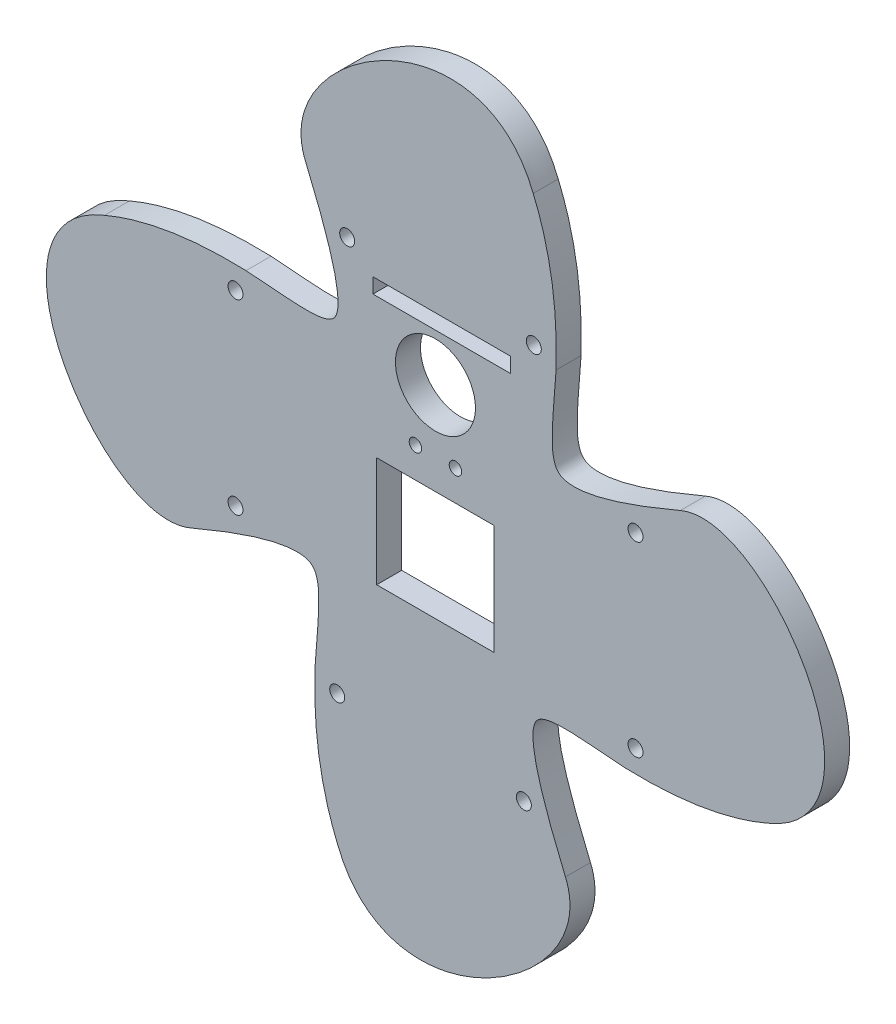
SolidWorks part; units mm, degrees
ref_plane "Front Plane" through (0, 0, 0) normal (0, 0, 1) x (1, 0, 0)
ref_plane "Top Plane" through (0, 0, 0) normal (0, 1, 0) x (1, 0, 0)
ref_plane "Right Plane" through (0, 0, 0) normal (1, 0, 0) x (0, 0, -1)
sketch "Sketch1" plane through (0, 0, 0) normal (0, 0, 1) x (1, 0, 0)
  line L0 (15.9859, 132.6591) -> (15.9859, 37.7698) construction
  line L5 (30.9859, 95.0039) -> (30.9859, 92.0039)
  line L6 (4.2359, 42.0321) -> (27.7359, 42.0321)
  line L7 (4.2359, 42.0321) -> (4.2359, 64.0321)
  line L8 (4.2359, 64.0321) -> (27.7359, 64.0321)
  line L9 (27.7359, 42.0321) -> (27.7359, 64.0321)
  line L10 (4.2359, 42.0321) -> (27.7359, 64.0321) construction
  line L11 (4.2359, 64.0321) -> (27.7359, 42.0321) construction
  line L16 (19.9859, 70.0821) -> (11.9859, 70.0821) construction
  line L17 (-27.7641, 70.6243) -> (-27.7641, 37.6243) construction
  line L18 (3.4859, 95.0039) -> (28.4859, 95.0039) construction
  line L19 (3.4859, 95.0039) -> (3.4859, 92.0039)
  line L20 (3.4859, 92.0039) -> (28.4859, 92.0039) construction
  line L21 (28.4859, 95.0039) -> (28.4859, 92.0039) construction
  line L22 (3.4859, 95.0039) -> (28.4859, 92.0039) construction
  line L23 (3.4859, 92.0039) -> (28.4859, 95.0039) construction
  line L24 (30.9859, 92.0039) -> (3.4859, 92.0039)
  line L25 (3.4859, 95.0039) -> (30.9859, 95.0039)
  line L26 (-0.5141, 92.0039) -> (32.4859, 92.0039) construction
  line L27 (-0.5141, 92.0039) -> (-0.5141, 124.0039) construction
  line L28 (-0.5141, 124.0039) -> (32.4859, 124.0039) construction
  line L29 (32.4859, 92.0039) -> (32.4859, 124.0039) construction
  line L30 (-0.5141, 92.0039) -> (32.4859, 124.0039) construction
  line L31 (-0.5141, 124.0039) -> (32.4859, 92.0039) construction
  line L32 (27.7359, 70.6243) -> (59.7359, 70.6243) construction
  line L33 (27.7359, 70.6243) -> (27.7359, 37.6243) construction
  line L34 (27.7359, 37.6243) -> (59.7359, 37.6243) construction
  line L35 (59.7359, 70.6243) -> (59.7359, 37.6243) construction
  line L36 (4.2359, 37.6243) -> (-27.7641, 37.6243) construction
  line L37 (4.2359, 70.6243) -> (4.2359, 37.6243) construction
  line L38 (4.2359, 70.6243) -> (-27.7641, 70.6243) construction
  circle A0 centre (15.9859, 82.5039) radius 8
  circle A4 centre (11.9859, 70.0821) radius 1.25
  circle A5 centre (19.9859, 70.0821) radius 1.25
  circle A6 centre (19.9859, 70.0821) radius 5.05 construction
  spline S0 degree 3 poles (16.8614, 61.071) (19.1525, 88.4527) (-4.5658, 100.1358) (-8.1539, 109.0166) knots 0 0 0 0 1 1 1 1 construction
  spline S1 degree 3 poles (-8.1539, 109.0166) (-14.7239, 124.1957) (23.9896, 149.4382) (33.6812, 124.7097) knots 0 0 0 0 1 1 1 1 construction
  spline S2 degree 3 poles (33.6812, 124.7097) (42.7198, 103.6961) (38.6714, 66.4651) (16.8614, 61.071) knots 0 0 0 0 1 1 1 1 construction
  spline S3 degree 3 poles (81.4407, 41.5775) (60.4271, 32.5389) (23.1961, 36.5873) (17.802, 58.3973) knots 0 0 0 0 1 1 1 1 construction
  spline S4 degree 3 poles (17.802, 58.3973) (45.1837, 56.1063) (56.8668, 79.8246) (65.7477, 83.4126) knots 0 0 0 0 1 1 1 1 construction
  spline S5 degree 3 poles (65.7477, 83.4126) (80.9267, 89.9827) (106.1692, 51.2692) (81.4407, 41.5775) knots 0 0 0 0 1 1 1 1 construction
  spline S6 degree 3 poles (-1.6915, -6.182) (-10.7301, 14.8316) (-6.6817, 52.0626) (15.1283, 57.4568) knots 0 0 0 0 1 1 1 1 construction
  spline S7 degree 3 poles (15.1283, 57.4568) (12.8373, 30.0751) (36.5556, 18.3919) (40.1436, 9.5111) knots 0 0 0 0 1 1 1 1 construction
  spline S8 degree 3 poles (40.1436, 9.5111) (46.7137, -5.668) (8.0002, -30.9104) (-1.6915, -6.182) knots 0 0 0 0 1 1 1 1 construction
  spline S9 degree 3 poles (-49.451, 76.9502) (-28.4374, 85.9888) (8.7936, 81.9404) (14.1878, 60.1304) knots 0 0 0 0 1 1 1 1 construction
  spline S10 degree 3 poles (14.1878, 60.1304) (-13.1939, 62.4215) (-24.8771, 38.7032) (-33.7579, 35.1151) knots 0 0 0 0 1 1 1 1 construction
  spline S11 degree 3 poles (-33.7579, 35.1151) (-48.937, 28.5451) (-74.1794, 67.2586) (-49.451, 76.9502) knots 0 0 0 0 1 1 1 1 construction
  spline S12 degree 3 poles (-8.1539, 109.0166) (5.8128, 76.0688) (-3.7824, 80.2696) (-21.9955, 81.376) knots 0 0 0 0 1 1 1 1 construction
  spline S13 degree 2 poles (-49.451, 76.9502) (-37.9198, 81.8915) (-21.9955, 81.376) knots 0 0 0 1 1 1 construction
  spline S14 degree 2 poles (33.6812, 124.7097) (38.6225, 113.1785) (38.107, 97.2542) knots 0 0 0 1 1 1 construction
  spline S15 degree 3 poles (65.7477, 83.4126) (32.7998, 69.446) (37.0006, 79.0411) (38.107, 97.2542) knots 0 0 0 0 1 1 1 1 construction
  spline S16 degree 2 poles (81.4407, 41.5775) (69.9096, 36.6362) (53.9852, 37.1517) knots 0 0 0 1 1 1 construction
  spline S17 degree 3 poles (40.1436, 9.5111) (26.177, 42.4589) (35.7722, 38.2582) (53.9852, 37.1517) knots 0 0 0 0 1 1 1 1 construction
  spline S18 degree 2 poles (-1.6915, -6.182) (-6.6328, 5.3492) (-6.1173, 21.2735) knots 0 0 0 1 1 1 construction
  spline S19 degree 3 poles (-33.7579, 35.1151) (-0.8101, 49.0817) (-5.0108, 39.4866) (-6.1173, 21.2735) knots 0 0 0 0 1 1 1 1 construction
  spline S20 degree 1 poles (-3.542, -6.9412) (-8.1153, 21.3665) knots 0 0 1 1 construction
  spline S21 degree 1 poles (-32.9708, 33.2765) (-8.1153, 21.3665) knots 0 0 1 1 construction
  spline S22 degree 1 poles (-32.9708, 33.2765) (-50.2102, 78.8007) knots 0 0 1 1 construction
  spline S23 degree 1 poles (-50.2102, 78.8007) (-21.9025, 83.3741) knots 0 0 1 1 construction
  spline S24 degree 1 poles (-9.9925, 108.2295) (-21.9025, 83.3741) knots 0 0 1 1 construction
  spline S25 degree 1 poles (-9.9925, 108.2295) (35.5317, 125.469) knots 0 0 1 1 construction
  spline S26 degree 1 poles (35.5317, 125.469) (40.1051, 97.1612) knots 0 0 1 1 construction
  spline S27 degree 1 poles (64.9605, 85.2512) (40.1051, 97.1612) knots 0 0 1 1 construction
  spline S28 degree 1 poles (64.9605, 85.2512) (82.2, 39.727) knots 0 0 1 1 construction
  spline S29 degree 1 poles (82.2, 39.727) (53.8922, 35.1537) knots 0 0 1 1 construction
  spline S30 degree 1 poles (41.9822, 10.2982) (53.8922, 35.1537) knots 0 0 1 1 construction
  spline S31 degree 1 poles (41.9822, 10.2982) (-3.542, -6.9412) knots 0 0 1 1 construction
  spline S32 degree 2 poles (-3.542, -6.9412) (-8.667, 5.1045) (-8.1153, 21.3665) knots 0.001185 0.001185 0.001185 1.000889 1.000889 1.000889
  spline S33 degree 3 poles (-8.1153, 21.3665) (-8.0808, 21.9348) (-8.0041, 23.0851) (-7.8384, 25.271) (-7.6232, 27.8547) (-7.4142, 30.6638) (-7.2734, 33.9809) (-7.4626, 36.563) (-8.03, 38.1615) (-8.5526, 38.8833) (-9.2308, 39.3726) (-10.4146, 39.7436) (-12.2957, 39.8323) (-14.8912, 39.5173) (-18.2102, 38.7418) (-21.5997, 37.6853) (-24.7056, 36.582) (-27.2365, 35.6235) (-29.5238, 34.711) (-31.4515, 33.9167) (-32.4695, 33.489) (-32.9708, 33.2765) knots 0.000067 0.000067 0.000067 0.000067 0.031331 0.062595 0.125123 0.187652 0.25018 0.375236 0.437764 0.500292 0.56282 0.625349 0.687877 0.750405 0.812933 0.875461 0.906725 0.937989 0.969253 0.984885 1.000517 1.000517 1.000517 1.000517
  spline S34 degree 3 poles (-32.9708, 33.2765) (-33.5431, 33.0293) (-34.7402, 32.6308) (-37.1706, 32.26) (-40.245, 32.5176) (-43.8292, 33.7656) (-48.4091, 36.4387) (-53.6534, 41.3427) (-58.6696, 48.875) (-61.2463, 55.8816) (-61.9576, 61.5623) (-61.6934, 65.7665) (-60.4936, 69.7927) (-58.61, 72.8489) (-56.548, 75.0101) (-54.7267, 76.4675) (-52.9768, 77.5338) (-51.4462, 78.2888) (-50.6218, 78.6388) (-50.2102, 78.8007) knots 0.000131 0.000131 0.000131 0.000131 0.031365 0.0626 0.125069 0.187538 0.250007 0.374945 0.499882 0.62482 0.687289 0.749758 0.812227 0.874696 0.905931 0.937165 0.9684 0.984017 0.999634 0.999634 0.999634 0.999634
  spline S35 degree 2 poles (-50.2102, 78.8007) (-38.1645, 83.9257) (-21.9025, 83.3741) knots 0.001185 0.001185 0.001185 1.000889 1.000889 1.000889
  spline S36 degree 3 poles (-21.9025, 83.3741) (-21.3342, 83.3395) (-20.1839, 83.2629) (-17.998, 83.0971) (-15.4143, 82.882) (-12.6052, 82.6729) (-9.2881, 82.5321) (-6.706, 82.7214) (-5.1075, 83.2888) (-4.3857, 83.8114) (-3.8964, 84.4895) (-3.5254, 85.6733) (-3.4367, 87.5545) (-3.7516, 90.15) (-4.5272, 93.469) (-5.5837, 96.8584) (-6.687, 99.9644) (-7.6455, 102.4952) (-8.558, 104.7826) (-9.3523, 106.7102) (-9.78, 107.7283) (-9.9925, 108.2295) knots 0.000067 0.000067 0.000067 0.000067 0.031331 0.062595 0.125123 0.187652 0.25018 0.375236 0.437764 0.500292 0.56282 0.625349 0.687877 0.750405 0.812933 0.875461 0.906725 0.937989 0.969253 0.984885 1.000517 1.000517 1.000517 1.000517
  spline S37 degree 3 poles (-9.9925, 108.2295) (-10.2397, 108.8018) (-10.6382, 109.999) (-11.009, 112.4293) (-10.7514, 115.5038) (-9.5034, 119.0879) (-6.8302, 123.6679) (-1.9263, 128.9121) (5.606, 133.9284) (12.6126, 136.505) (18.2933, 137.2164) (22.4975, 136.9521) (26.5237, 135.7524) (29.5799, 133.8688) (31.7411, 131.8068) (33.1985, 129.9855) (34.2648, 128.2355) (35.0198, 126.7049) (35.3698, 125.8805) (35.5317, 125.469) knots 0.000131 0.000131 0.000131 0.000131 0.031365 0.0626 0.125069 0.187538 0.250007 0.374945 0.499882 0.62482 0.687289 0.749758 0.812227 0.874696 0.905931 0.937165 0.9684 0.984017 0.999634 0.999634 0.999634 0.999634
  spline S38 degree 2 poles (35.5317, 125.469) (40.6567, 113.4233) (40.1051, 97.1612) knots 0.001185 0.001185 0.001185 1.000889 1.000889 1.000889
  spline S39 degree 3 poles (40.1051, 97.1612) (40.0706, 96.5929) (39.9939, 95.4427) (39.8281, 93.2567) (39.613, 90.6731) (39.404, 87.8639) (39.2632, 84.5468) (39.4524, 81.9648) (40.0198, 80.3662) (40.5424, 79.6444) (41.2205, 79.1551) (42.4043, 78.7842) (44.2855, 78.6954) (46.881, 79.0104) (50.2, 79.7859) (53.5894, 80.8424) (56.6954, 81.9457) (59.2262, 82.9042) (61.5136, 83.8168) (63.4412, 84.611) (64.4593, 85.0388) (64.9605, 85.2512) knots 0.000067 0.000067 0.000067 0.000067 0.031331 0.062595 0.125123 0.187652 0.25018 0.375236 0.437764 0.500292 0.56282 0.625349 0.687877 0.750405 0.812933 0.875461 0.906725 0.937989 0.969253 0.984885 1.000517 1.000517 1.000517 1.000517
  spline S40 degree 3 poles (64.9605, 85.2512) (65.5328, 85.4985) (66.73, 85.8969) (69.1603, 86.2678) (72.2348, 86.0101) (75.8189, 84.7621) (80.3989, 82.089) (85.6432, 77.1851) (90.6594, 69.6528) (93.236, 62.6461) (93.9474, 56.9654) (93.6831, 52.7613) (92.4834, 48.735) (90.5998, 45.6788) (88.5378, 43.5177) (86.7165, 42.0602) (84.9665, 40.9939) (83.4359, 40.2389) (82.6115, 39.8889) (82.2, 39.727) knots 0.000131 0.000131 0.000131 0.000131 0.031365 0.0626 0.125069 0.187538 0.250007 0.374945 0.499882 0.62482 0.687289 0.749758 0.812227 0.874696 0.905931 0.937165 0.9684 0.984017 0.999634 0.999634 0.999634 0.999634
  spline S41 degree 2 poles (82.2, 39.727) (70.1543, 34.602) (53.8922, 35.1537) knots 0.001185 0.001185 0.001185 1.000889 1.000889 1.000889
  spline S42 degree 3 poles (53.8922, 35.1537) (53.324, 35.1882) (52.1737, 35.2649) (49.9877, 35.4306) (47.4041, 35.6458) (44.5949, 35.8548) (41.2778, 35.9956) (38.6958, 35.8064) (37.0972, 35.239) (36.3754, 34.7163) (35.8861, 34.0382) (35.5152, 32.8544) (35.4265, 30.9732) (35.7414, 28.3778) (36.5169, 25.0588) (37.5734, 21.6693) (38.6767, 18.5634) (39.6352, 16.0325) (40.5478, 13.7452) (41.342, 11.8175) (41.7698, 10.7995) (41.9822, 10.2982) knots 0.000067 0.000067 0.000067 0.000067 0.031331 0.062595 0.125123 0.187652 0.25018 0.375236 0.437764 0.500292 0.56282 0.625349 0.687877 0.750405 0.812933 0.875461 0.906725 0.937989 0.969253 0.984885 1.000517 1.000517 1.000517 1.000517
  spline S43 degree 3 poles (41.9822, 10.2982) (42.2295, 9.7259) (42.6279, 8.5288) (42.9988, 6.0984) (42.7411, 3.024) (41.4931, -0.5602) (38.82, -5.1401) (33.9161, -10.3844) (26.3838, -15.4006) (19.3771, -17.9773) (13.6965, -18.6886) (9.4923, -18.4244) (5.466, -17.2246) (2.4098, -15.341) (0.2487, -13.279) (-1.2087, -11.4577) (-2.2751, -9.7078) (-3.0301, -8.1772) (-3.3801, -7.3528) (-3.542, -6.9412) knots 0.000131 0.000131 0.000131 0.000131 0.031365 0.0626 0.125069 0.187538 0.250007 0.374945 0.499882 0.62482 0.687289 0.749758 0.812227 0.874696 0.905931 0.937165 0.9684 0.984017 0.999634 0.999634 0.999634 0.999634
  point P0 (15.9859, 53.0321)
  point P12 (19.9859, 65.0321)
  point P14 (15.9859, 108.0039)
  point P17 (15.9859, 93.5039)
  point P23 (15.9859, 74.5039)
  point P24 (15.9859, 90.5039)
  point P25 (15.9859, 70.0821)
  point P44 (15.9949, 59.2639)
  point P67 (0, 0)
  dimension "D1" = 16
  dimension "D5" = 2.5
  dimension "D7" = 3.8
  dimension "D2" = 25
  dimension "D3" = 15
  dimension "D4" = 3
  dimension "D6" = 8
  dimension "D8" = 1.5
  dimension "D9" = 1
  dimension "D10" = 22
  dimension "D11" = 23.5
  dimension "D12" = 32
  dimension "D13" = 33
  dimension "D14" = 33
  dimension "D15" = 32
  dimension "D16" = 2
extrude "Boss-Extrude1" add sketch "Sketch1" along normal blind 5
sketch "Sketch2" plane through (0, 0, 5) normal (0, 0, 1) x (1, 0, 0)
  line L0 (-50.2102, 78.8007) -> (82.2, 39.727) construction
  line L1 (-1.6711, 99.2639) -> (35.6529, 99.2639) construction
  line L2 (64.9605, 85.2512) -> (-32.9708, 33.2765) construction
  circle A0 centre (-1.6711, 99.2639) radius 1.5
  circle A1 centre (35.6529, 99.2639) radius 1.5
  circle A2 centre (-1.6711, 99.2639) radius 4.5 construction
  circle A3 centre (35.6529, 99.2639) radius 4.5 construction
  circle A4 centre (55.9949, 76.9298) radius 1.5
  circle A5 centre (55.9949, 39.6059) radius 1.5
  circle A6 centre (33.6608, 19.2639) radius 1.5
  circle A7 centre (-3.6631, 19.2639) radius 1.5
  circle A8 centre (-24.0051, 41.5979) radius 1.5
  circle A9 centre (-24.0051, 78.9219) radius 1.5
  parabola Q37 (40.1051, 97.1612) -> (35.5317, 125.469) focus (11.6295, 121.4725) apex (30.0153, 135.1288) construction
  parabola Q38 (40.1051, 97.1612) -> (35.5317, 125.469) focus (11.6295, 121.4725) apex (30.0153, 135.1288) construction
  spline S2 degree 3 poles (-9.9925, 108.2295) (-9.78, 107.7283) (-9.3523, 106.7102) (-8.558, 104.7826) (-7.6455, 102.4952) (-6.687, 99.9644) (-5.5837, 96.8584) (-4.5272, 93.469) (-3.7516, 90.15) (-3.4367, 87.5545) (-3.5254, 85.6733) (-3.8964, 84.4895) (-4.3857, 83.8114) (-5.1075, 83.2888) (-6.706, 82.7214) (-9.2881, 82.5321) (-12.6052, 82.6729) (-15.4143, 82.882) (-17.998, 83.0971) (-20.1839, 83.2629) (-21.3342, 83.3395) (-21.9025, 83.3741) knots 0.000067 0.000067 0.000067 0.000067 0.015699 0.031331 0.062595 0.093859 0.125123 0.187652 0.25018 0.312708 0.375236 0.437764 0.500292 0.56282 0.625349 0.750405 0.812933 0.875461 0.937989 0.969253 1.000517 1.000517 1.000517 1.000517 construction
  point P0 (15.9949, 59.2639)
  point P4 (-50.2102, 78.8007)
  point P30 (40.1529, 99.2639)
  dimension "D1" = 3
  dimension "D4" = 3
  dimension "D2" = 40
  dimension "D3" = 4
extrude "Cut-Extrude1" cut sketch "Sketch2" against normal up to next
